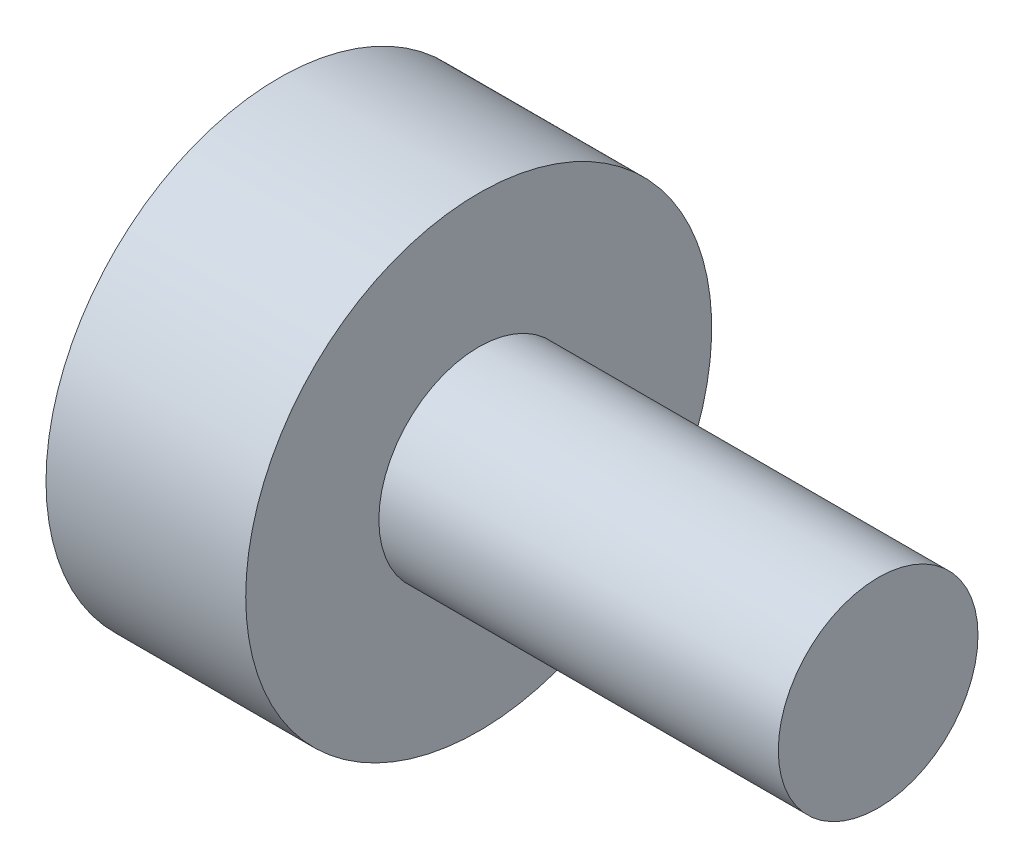
SolidWorks part; units mm, degrees
ref_plane "Спереди" through (0, 0, 0) normal (0, 0, 1) x (1, 0, 0)
ref_plane "Сверху" through (0, 0, 0) normal (0, 1, 0) x (1, 0, 0)
ref_plane "Справа" through (0, 0, 0) normal (1, 0, 0) x (0, 0, -1)
sketch "Эскиз1" plane through (0, 0, 0) normal (0, 0, 1) x (1, 0, 0)
  line L0 (0, 0) -> (100, 0)
  line L1 (0, 0) -> (0, 20)
  line L2 (0, 20) -> (10, 20)
  line L3 (10, 20) -> (10, 35)
  line L4 (10, 35) -> (40, 35)
  line L5 (40, 35) -> (40, 15)
  line L6 (40, 15) -> (100, 15)
  line L7 (100, 0) -> (100, 15)
revolve "Повернуть1" add sketch "Эскиз1" angle 360 about L0
sketch "Эскиз2" plane through (0, 0, 0) normal (1, 0, 0) x (0, 0, -1)
  circle A0 centre (0, 0) radius 4.25
extrude "Вырез-Вытянуть1" cut sketch "Эскиз2" along normal blind 20
